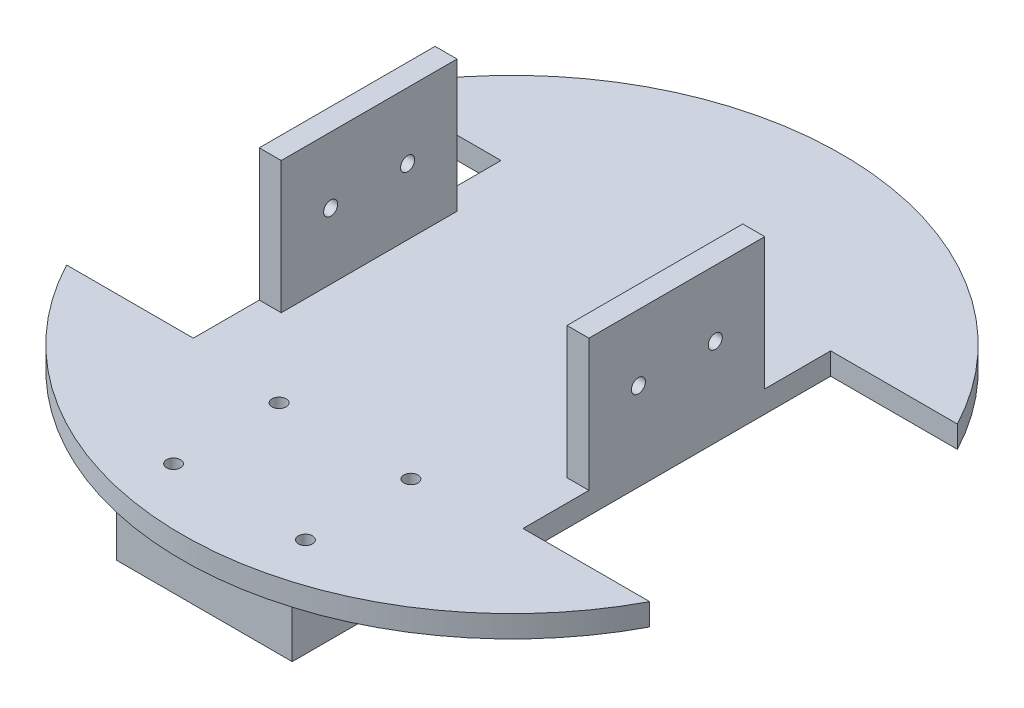
SolidWorks part; units mm, degrees
ref_plane "Front Plane" through (0, 0, 0) normal (0, 0, 1) x (1, 0, 0)
ref_plane "Top Plane" through (0, 0, 0) normal (0, 1, 0) x (1, 0, 0)
ref_plane "Right Plane" through (0, 0, 0) normal (1, 0, 0) x (0, 0, -1)
sketch "Sketch1" plane through (0, 0, 0) normal (0, 1, 0) x (1, 0, 0)
  circle A0 centre (0, 0) radius 75
  dimension "D1" = 150
extrude "Boss-Extrude2" add sketch "Sketch1" along normal blind 5 contours A0
sketch "Sketch5" plane through (0, 5, 0) normal (0, 1, 0) x (1, 0, 0)
  line L0 (0, 0) -> (162.2631, 0) construction
  line L1 (0, 0) -> (0, 110.711) construction
  line L2 (37.5, 35) -> (72.5, 35)
  line L3 (37.5, 35) -> (37.5, -35)
  line L4 (37.5, -35) -> (72.5, -35)
  line L5 (72.5, 35) -> (72.5, -35)
  line L6 (37.5, 35) -> (72.5, -35) construction
  line L7 (37.5, -35) -> (72.5, 35) construction
  line L8 (-72.5, 35) -> (-72.5, -35)
  line L9 (-37.5, -35) -> (-72.5, -35)
  line L10 (-37.5, 35) -> (-37.5, -35)
  line L11 (-37.5, 35) -> (-72.5, 35)
  point P3 (55, 0)
  dimension "D1" = 70
  dimension "D2" = 35
  dimension "D3" = 55
extrude "Cut-Extrude1" cut sketch "Sketch5" against normal through all
sketch "Sketch6" plane through (0, 5, 0) normal (0, 1, 0) x (1, 0, 0)
  line L0 (-37.5, -35) -> (-37.5, 35) construction
  line L1 (-37.5, 20) -> (-32.5, 20)
  line L2 (-37.5, 20) -> (-37.5, -20)
  line L3 (-37.5, -20) -> (-32.5, -20)
  line L4 (-32.5, 20) -> (-32.5, -20)
  point P4 (-37.5, 0)
  dimension "D1" = 5
  dimension "D2" = 40
extrude "Boss-Extrude3" add sketch "Sketch6" along normal blind 30
sketch "Sketch7" plane through (-32.5, 0, 0) normal (1, 0, 0) x (0, 0, -1)
  line L0 (-20, 35) -> (-20, 5) construction
  line L1 (-20, 5) -> (20, 5) construction
  circle A0 centre (-8.75, 20) radius 1.6
  circle A1 centre (8.75, 20) radius 1.6
  point P8 (0, 0)
  dimension "D1" = 3.2
  dimension "D2" = 3.2
  dimension "D3" = 17.5
  dimension "D4" = 15
  dimension "D5" = 11.25
extrude "Cut-Extrude2" cut sketch "Sketch7" against normal through all
mirror "Mirror1" about plane through (0, 0, 0) normal (1, 0, 0) of "Boss-Extrude3", "Cut-Extrude2"
delete or keep bodies "Body-Delete/Keep 1" type delete bodies bodies 104
delete or keep bodies "Body-Delete/Keep 2" type delete bodies bodies 105
sketch "Sketch8" plane through (0, 0, 0) normal (0, -1, 0) x (1, 0, 0)
  line L1 (-20, 70) -> (20, 70)
  line L2 (-20, 70) -> (-20, 30)
  line L3 (-20, 30) -> (20, 30)
  line L4 (20, 70) -> (20, 30)
  line L5 (-20, 70) -> (20, 30) construction
  line L6 (-20, 30) -> (20, 70) construction
  point P0 (0, 50)
  dimension "D1" = 40
  dimension "D2" = 40
  dimension "D3" = 50
extrude "Boss-Extrude5" add sketch "Sketch8" along normal blind 12.5
sketch "Sketch9" plane through (0, -12.5, 0) normal (0, -1, 0) x (1, 0, 0)
  line L1 (-20, 70) -> (-20, 30) construction
  line L3 (20, 70) -> (-20, 70) construction
  circle A0 centre (-15, 62) radius 1.6
  circle A1 centre (15, 62) radius 1.6
  circle A2 centre (-15, 38) radius 1.6
  circle A3 centre (15, 38) radius 1.6
  point P8 (0, 0)
  point P9 (0, 0)
  point P10 (0, 0)
  dimension "D1" = 3.2
  dimension "D2" = 3.2
  dimension "D3" = 3.2
  dimension "D4" = 3.2
  dimension "D5" = 30
  dimension "D6" = 30
  dimension "D7" = 24
  dimension "D8" = 5
  dimension "D9" = 8
extrude "Cut-Extrude3" cut sketch "Sketch9" against normal through all
sketch "Sketch10" plane through (0, 5, 0) normal (0, 1, 0) x (1, 0, 0)
  line L0 (-32.5, -20) -> (-32.5, 20) construction
  line L1 (-26, 23) -> (26, 23) construction
  line L2 (-26, 23) -> (-26, -23) construction
  line L3 (-26, -23) -> (26, -23) construction
  line L4 (26, 23) -> (26, -23) construction
  line L5 (-26, 23) -> (26, -23) construction
  line L6 (-26, -23) -> (26, 23) construction
  line L7 (32.5, -20) -> (32.5, 20) construction
  circle A0 centre (26, 23) radius 1.6
  circle A1 centre (-26, 23) radius 1.6
  circle A2 centre (-26, -23) radius 1.6
  circle A3 centre (26, -23) radius 1.6
  circle A4 centre (-22.5, 0) radius 6
  circle A5 centre (22.5, 0) radius 6
  point P0 (0, 0)
  point P16 (-32.5, 0)
  point P19 (32.5, 0)
  dimension "D3" = 3.2
  dimension "D4" = 3.2
  dimension "D5" = 3.2
  dimension "D6" = 3.2
  dimension "D9" = 12
  dimension "D10" = 12
  dimension "D1" = 52
  dimension "D2" = 46
  dimension "D7" = 10
  dimension "D8" = 10
